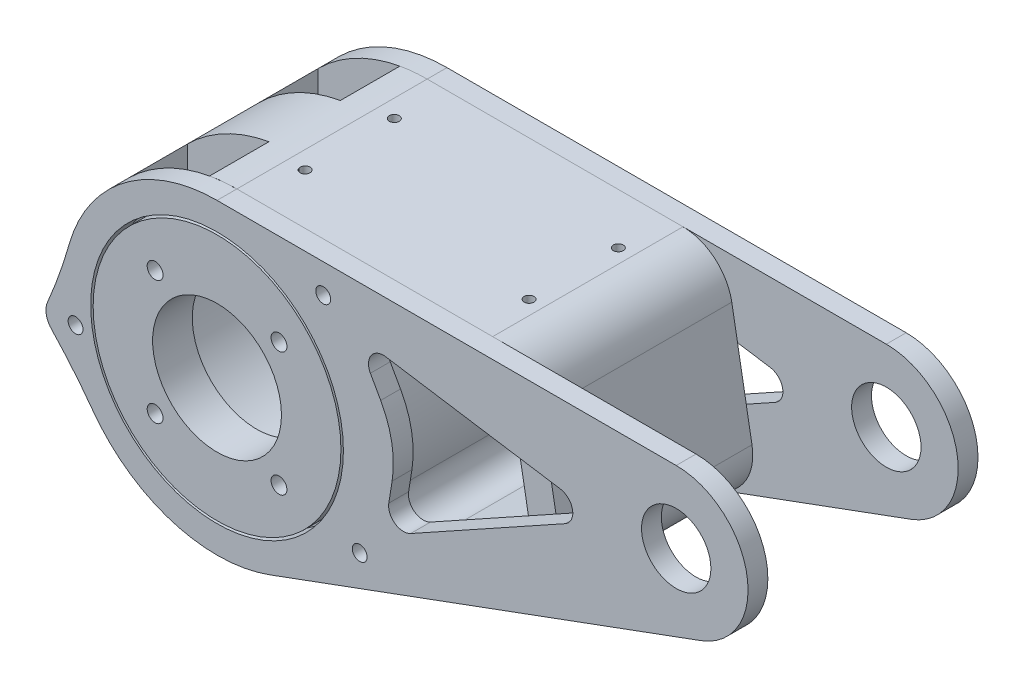
SolidWorks part; units mm, degrees
ref_plane "前视基准面" through (0, 0, 0) normal (0, 0, 1) x (1, 0, 0)
ref_plane "上视基准面" through (0, 0, 0) normal (0, 1, 0) x (1, 0, 0)
ref_plane "右视基准面" through (0, 0, 0) normal (1, 0, 0) x (0, 0, -1)
other "Configuration Table"
sketch "草图1" plane through (0, 0, 0) normal (0, 0, 1) x (1, 0, 0)
  circle A0 centre (0, 0) radius 21
  circle A1 centre (0, 0) radius 31
  dimension "D1" = 42
  dimension "D2" = 10
extrude "凸台-拉伸1" add sketch "草图1" along normal mid plane 46.4
sketch "草图2" plane through (0, 0, 23.2) normal (0, 0, 1) x (1, 0, 0)
  circle A0 centre (0, 0) radius 31
  circle A1 centre (0, 0) radius 13
  circle A2 centre (0, 0) radius 31 construction
  dimension "D2" = 26
extrude "凸台-拉伸2" add sketch "草图2" against normal blind 8
sketch "草图3" plane through (0, 0, 23.2) normal (0, 0, 1) x (1, 0, 0)
  line L1 (-12.5, 12.5) -> (12.5, 12.5) construction
  line L2 (-12.5, 12.5) -> (-12.5, -12.5) construction
  line L3 (-12.5, -12.5) -> (12.5, -12.5) construction
  line L4 (12.5, 12.5) -> (12.5, -12.5) construction
  line L5 (-12.5, 12.5) -> (12.5, -12.5) construction
  line L6 (-12.5, -12.5) -> (12.5, 12.5) construction
  circle A0 centre (-12.5, 12.5) radius 1.6
  circle A1 centre (-12.5, -12.5) radius 1.6
  circle A2 centre (12.5, -12.5) radius 1.6
  circle A3 centre (12.5, 12.5) radius 1.6
  point P0 (0, 0)
  dimension "D2" = 3.2
  dimension "D1" = 25
extrude "切除-拉伸1" cut sketch "草图3" against normal through all
sketch "草图4" plane through (0, 0, 23.2) normal (0, 0, 1) x (1, 0, 0)
  line L0 (0, 31) -> (174.0706, 31) construction
  line L1 (10.7021, -29.0941) -> (174.0706, 31) construction
  line L2 (0, 31) -> (60, 31)
  line L3 (10.7021, -29.0941) -> (67.0132, -8.3804)
  line L4 (60, 31) -> (67.0132, -8.3804)
  circle A0 centre (0, 0) radius 31 construction
  arc A1 (0, 31) -> (10.7021, -29.0941) centre (0, 0) ccw construction
  arc A4 (0, 31) -> (10.7021, -29.0941) centre (0, 0) cw
  dimension "D2" = 40
  dimension "D1" = 60
extrude "凸台-拉伸3" add sketch "草图4" against normal up to surface (46.4 mm away) up to face at (31, 0, -23.2)
fillet "圆角1" radius 10 2 edges at (67.0132, -8.3804, 0) (60, 31, 0)
sketch "草图7" plane through (0, 0, 23.2) normal (0, 0, 1) x (1, 0, 0)
  line L0 (65.5446, -0.1337) -> (61.4686, 22.7533) construction
  line L1 (10.7021, -29.0941) -> (59.1517, -11.2722) construction
  line L2 (51.6235, 31) -> (0, 31) construction
  line L3 (65.5446, -0.1337) -> (61.4686, 22.7533)
  line L4 (10.7021, -29.0941) -> (59.1517, -11.2722)
  line L5 (51.6235, 31) -> (0, 31)
  arc A0 (61.4686, 22.7533) -> (51.6235, 31) centre (51.6235, 21) ccw construction
  arc A1 (59.1517, -11.2722) -> (65.5446, -0.1337) centre (55.6995, -1.887) ccw construction
  arc A2 (0, 31) -> (10.7021, -29.0941) centre (0, 0) ccw construction
  arc A3 (61.4686, 22.7533) -> (51.6235, 31) centre (51.6235, 21) ccw
  arc A4 (59.1517, -11.2722) -> (65.5446, -0.1337) centre (55.6995, -1.887) ccw
  arc A5 (0, 31) -> (10.7021, -29.0941) centre (0, 0) ccw
  circle A6 centre (0, 0) radius 25
  dimension "D1" = 50
extrude "切除-拉伸4" cut sketch "草图7" against normal blind 4
ref_plane "基准面1" through (0, 0, 0) normal (0, 0, 1) x (1, 0, 0)
mirror "镜向1" about plane through (0, 0, 0) normal (0, 0, 1) of "切除-拉伸4"
sketch "草图8" plane through (0, 0, 19.2) normal (0, 0, 1) x (1, 0, 0)
  line L0 (18.3303, 25) -> (54.9741, 25)
  line L1 (25.834, -17.1348) -> (60.225, -4.4843)
  line L2 (10.7021, -29.0941) -> (59.1517, -11.2722) construction
  line L3 (54.9741, 25) -> (60.225, -4.4843)
  line L4 (65.5446, -0.1337) -> (61.4686, 22.7533) construction
  line L5 (51.6235, 31) -> (0, 31) construction
  circle A0 centre (0, 0) radius 31 construction
  arc A1 (0, 31) -> (10.7021, -29.0941) centre (0, 0) ccw construction
  arc A2 (18.3303, 25) -> (25.834, -17.1348) centre (0, 0) cw
  dimension "D1" = 6
  dimension "D2" = 6
  dimension "D3" = 6
extrude "切除-拉伸5" cut sketch "草图8" against normal through all
fillet "圆角2" radius 5 4 edges at (60.225, -4.4843, 0) (54.9741, 25, 0) (25.834, -17.1348, 0) (18.3303, 25, 0)
sketch "草图9" plane through (0, 0, 19.2) normal (0, 0, 1) x (1, 0, 0)
  line L15 (51.6235, 31) -> (0, 31)
  line L16 (10.7021, -29.0941) -> (59.1517, -11.2722)
  line L17 (65.5446, -0.1337) -> (61.4686, 22.7533)
  line L21 (51.6235, 31) -> (0, 31)
  line L22 (10.7021, -29.0941) -> (97.6563, 2.8915)
  line L25 (51.6235, 31) -> (92.6505, 31)
  arc A12 (92.6505, 31) -> (97.6563, 2.8915) centre (92.6505, 16.5) cw
  circle A13 centre (92.6505, 16.5) radius 7
  circle A14 centre (0, 0) radius 25.5
  arc A15 (61.4686, 22.7533) -> (51.6235, 31) centre (51.6235, 21) ccw
  arc A19 (0, 31) -> (10.7021, -29.0941) centre (0, 0) ccw
  arc A20 (59.1517, -11.2722) -> (65.5446, -0.1337) centre (55.6995, -1.887) ccw
  arc A22 (0, 31) -> (10.7021, -29.0941) centre (0, 0) ccw
  dimension "D2" = 14
  dimension "D3" = 14.5
  dimension "D4" = 51
  dimension "D1" = 0
extrude "凸台-拉伸4" add sketch "草图9" along normal blind 4 separate body
mirror "镜向4" about plane through (0, 0, 0) normal (0, 0, 1) of bodies 115
sketch "草图10" plane through (0, 0, 23.2) normal (0, 0, 1) x (1, 0, 0)
  line L0 (0, 0) -> (63.3136, 11.2754) construction
  line L2 (59.4906, -0.361) -> (55.7084, 20.8767) construction
  line L3 (28.7869, -16.2038) -> (21.4231, 25.1456) construction
  circle A1 centre (0, 0) radius 25.5 construction
  circle A2 centre (21.4231, 25.1456) radius 1.5
  circle A3 centre (28.7869, -16.2038) radius 1.5
  point P1 (57.5995, 10.2578)
  point P10 (25.105, 4.4709)
  dimension "D1" = 3
  dimension "D2" = 21
extrude "切除-拉伸6" cut sketch "草图10" against normal through all
sketch "草图13" plane through (0, 0, 19.2) normal (0, 0, 1) x (1, 0, 0)
  line L0 (0, 0) -> (56.6929, 10.0964) construction
  line L2 (59.4906, -0.361) -> (55.7084, 20.8767) construction
  line L6 (51.6235, 31) -> (0, 31)
  line L7 (10.7021, -29.0941) -> (59.1517, -11.2722)
  line L8 (65.5446, -0.1337) -> (61.4686, 22.7533)
  arc A0 (-30.9656, -1.4601) -> (-29.5659, -9.3198) centre (-30.5198, -5.4352) ccw
  arc A1 (0, 31) -> (10.7021, -29.0941) centre (0, 0) ccw construction
  arc A5 (61.4686, 22.7533) -> (51.6235, 31) centre (51.6235, 21) ccw
  arc A6 (0, 31) -> (10.7021, -29.0941) centre (0, 0) ccw
  arc A7 (59.1517, -11.2722) -> (65.5446, -0.1337) centre (55.6995, -1.887) ccw
  arc A9 (-30.9656, -1.4601) -> (-29.5659, -9.3198) centre (0, 0) ccw
  point P1 (57.5995, 10.2578)
  dimension "D1" = 4
  dimension "D2" = 0
extrude "凸台-拉伸5" add sketch "草图13" against normal up to surface (38.4 mm away) up to face at (19.9231, 25.1456, -19.2)
fillet "圆角3" radius 100 2 edges at (-30.9656, -1.4601, 0) (-29.5659, -9.3198, 0)
sketch "草图14" plane through (0, 0, 19.2) normal (0, 0, 1) x (1, 0, 0)
  line L0 (0, 0) -> (57.1164, 10.1718) construction
  line L2 (59.4906, -0.361) -> (55.7084, 20.8767) construction
  circle A0 centre (-28.5508, -5.0846) radius 1.5
  point P3 (57.5995, 10.2578)
  dimension "D2" = 3
  dimension "D1" = 29
extrude "切除-拉伸8" cut sketch "草图14" against normal through all and the other way through all
sketch "草图16" plane through (0, 0, 23.2) normal (0, 0, 1) x (1, 0, 0)
  arc A0 (-25.0791, -18.2219) -> (-33.4221, -8.1878) centre (-105.9796, -77.0021) ccw construction
  arc A1 (-34.1939, -3.8538) -> (-33.4221, -8.1878) centre (-30.5198, -5.4352) ccw construction
  arc A2 (-34.1939, -3.8538) -> (-29.8279, 8.4436) centre (-126.0471, 35.6808) ccw construction
  arc A3 (-25.0791, -18.2219) -> (-33.4221, -8.1878) centre (-105.9796, -77.0021) ccw
  arc A4 (-34.1939, -3.8538) -> (-33.4221, -8.1878) centre (-30.5198, -5.4352) ccw
  arc A5 (-34.1939, -3.8538) -> (-29.8279, 8.4436) centre (-126.0471, 35.6808) ccw
  arc A6 (-29.8279, 8.4436) -> (-25.0791, -18.2219) centre (0, 0) ccw
  point P10 (-24.9702, -18.3708)
extrude "凸台-拉伸6" add sketch "草图16" against normal up to surface (4 mm away)
sketch "草图18" plane through (0, 0, 23.2) normal (0, 0, 1) x (1, 0, 0)
  line L0 (0, 0) -> (92.6505, 16.5) construction
  line L1 (27.9255, 21.6448) -> (36.4269, 6.4872)
  line L2 (36.4269, 6.4872) -> (33.681, -10.6734)
  line L3 (33.681, -10.6734) -> (77.8828, 13.87)
  line L4 (77.8828, 13.87) -> (27.9255, 21.6448)
  line L5 (21.4231, 25.1456) -> (51.1945, 9.1172) construction
  line L6 (28.7869, -16.2038) -> (51.1945, 9.1172) construction
  line L7 (27.9255, 21.6448) -> (33.681, -10.6734) construction
  dimension "D1" = 52
  dimension "D2" = 17.3789
  dimension "D3" = 15
  dimension "D4" = 15
extrude "切除-拉伸9" cut sketch "草图18" against normal through all
fillet "圆角4" radius 20 1 edges at (36.4269, 6.4872, 21.2)
fillet "圆角5" radius 3 3 edges at (77.8828, 13.87, 21.2) (33.681, -10.6734, 21.2) (27.9255, 21.6448, 21.2)
fillet "圆角6" radius 20 1 edges at (36.4269, 6.4872, -21.2)
fillet "圆角7" radius 3 3 edges at (77.8828, 13.87, -21.2) (33.681, -10.6734, -21.2) (27.9255, 21.6448, -21.2)
sketch "草图19" plane through (0, 0, 19.2) normal (0, 0, -1) x (-1, 0, 0)
  circle A0 centre (-92.6505, 16.5) radius 7
  circle A1 centre (-92.6505, 16.5) radius 7.8
  dimension "D1" = 15.6
extrude "凸台-拉伸7" add sketch "草图19" along normal blind 0.8 separate body
sketch "草图20" plane through (0, 0, 18.4) normal (0, 0, -1) x (-1, 0, 0)
  circle A0 centre (-92.6505, 16.5) radius 7
  circle A1 centre (-92.6505, 16.5) radius 4
  dimension "D1" = 8
extrude "凸台-拉伸8" add sketch "草图20" against normal blind 4
sketch "草图21" plane through (0, 31, 0) normal (0, 1, 0) x (1, 0, 0)
  line L0 (0, 19.2) -> (0, -19.2) construction
  line L1 (3.5708, 9) -> (48.7708, 9) construction
  line L2 (3.5708, 9) -> (3.5708, -9) construction
  line L3 (3.5708, -9) -> (48.7708, -9) construction
  line L4 (48.7708, 9) -> (48.7708, -9) construction
  line L5 (51.6235, -19.2) -> (51.6235, 19.2) construction
  line L6 (0, 0) -> (51.6235, 0) construction
  circle A0 centre (3.5708, 9) radius 1
  circle A1 centre (3.5708, -9) radius 1
  circle A2 centre (48.7708, -9) radius 1
  circle A3 centre (48.7708, 9) radius 1
  point P4 (0, 0)
  point P5 (51.6235, 0)
  dimension "D3" = 2
  dimension "D1" = 45.2
  dimension "D2" = 18
extrude "切除-拉伸10" cut sketch "草图21" against normal blind 10
delete or keep bodies "实体-删除/保留 1" type delete bodies bodies 131
sketch "草图22" plane through (0, 0, -23.2) normal (0, 0, -1) x (-1, 0, 0)
  arc A0 (33.4221, -8.1878) -> (25.0791, -18.2219) centre (105.9796, -77.0021) ccw construction
  arc A1 (33.4221, -8.1878) -> (34.1939, -3.8538) centre (30.5198, -5.4352) ccw construction
  arc A2 (29.8279, 8.4436) -> (34.1939, -3.8538) centre (126.0471, 35.6808) ccw construction
  arc A3 (33.4221, -8.1878) -> (25.0791, -18.2219) centre (105.9796, -77.0021) ccw
  arc A4 (33.4221, -8.1878) -> (34.1939, -3.8538) centre (30.5198, -5.4352) ccw
  arc A5 (29.8279, 8.4436) -> (34.1939, -3.8538) centre (126.0471, 35.6808) ccw
  arc A6 (29.8279, 8.4436) -> (25.0791, -18.2219) centre (0, 0) cw
  point P10 (25.0791, -18.3639)
extrude "凸台-拉伸9" add sketch "草图22" against normal blind 4
sketch "草图23" plane through (0, 0, 19.2) normal (0, 0, 1) x (1, 0, 0)
  line L0 (-22, 21.8403) -> (-22, 11.8743)
  line L1 (-5.5069, 30.5069) -> (0, 25)
  line L2 (0, 25) -> (0, 0) construction
  arc A0 (-22, 11.8743) -> (0, 25) centre (0, 0) cw
  circle A1 centre (0, 0) radius 25 construction
  arc A2 (-22, 21.8403) -> (-5.5069, 30.5069) centre (0, 0) cw
  arc A3 (0, 31) -> (-29.8279, 8.4436) centre (0, 0) ccw construction
  circle A4 centre (0, 0) radius 25 construction
  dimension "D1" = 45
  dimension "D2" = 22
extrude "切除-拉伸11" cut sketch "草图23" against normal blind 12
mirror "镜向5" about plane through (0, 0, 0) normal (0, 0, 1) of "切除-拉伸11"
